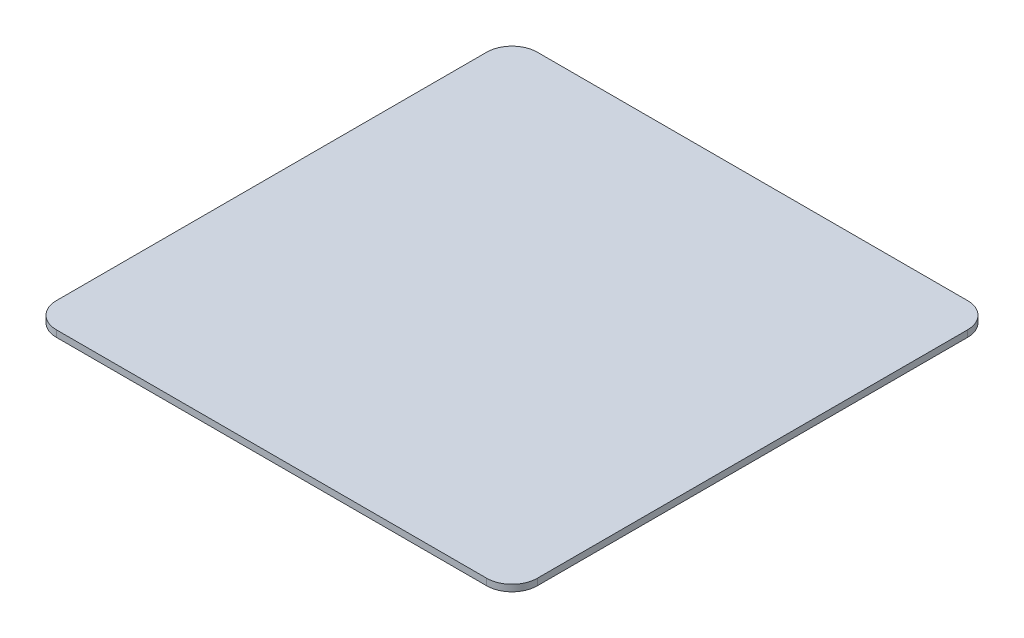
SolidWorks part; units mm, degrees
ref_plane "Front Plane" through (0, 0, 0) normal (0, 0, 1) x (1, 0, 0)
ref_plane "Top Plane" through (0, 0, 0) normal (0, 1, 0) x (1, 0, 0)
ref_plane "Right Plane" through (0, 0, 0) normal (1, 0, 0) x (0, 0, -1)
sketch "Sketch1" plane through (0, 0, 0) normal (0, 1, 0) x (1, 0, 0)
  line L1 (-47.5, -47.5) -> (47.5, -47.5)
  line L2 (-47.5, -47.5) -> (-47.5, 47.5)
  line L3 (-47.5, 47.5) -> (47.5, 47.5)
  line L4 (47.5, -47.5) -> (47.5, 47.5)
  line L5 (-47.5, -47.5) -> (47.5, 47.5) construction
  line L6 (-47.5, 47.5) -> (47.5, -47.5) construction
  point P0 (0, 0)
  dimension "D1" = 95
extrude "Boss-Extrude1" add sketch "Sketch1" along normal mid plane 1.3
fillet "Fillet1" radius 5 4 edges at (-47.5, 0, -47.5) (47.5, 0, -47.5) (47.5, 0, 47.5) (-47.5, 0, 47.5)
